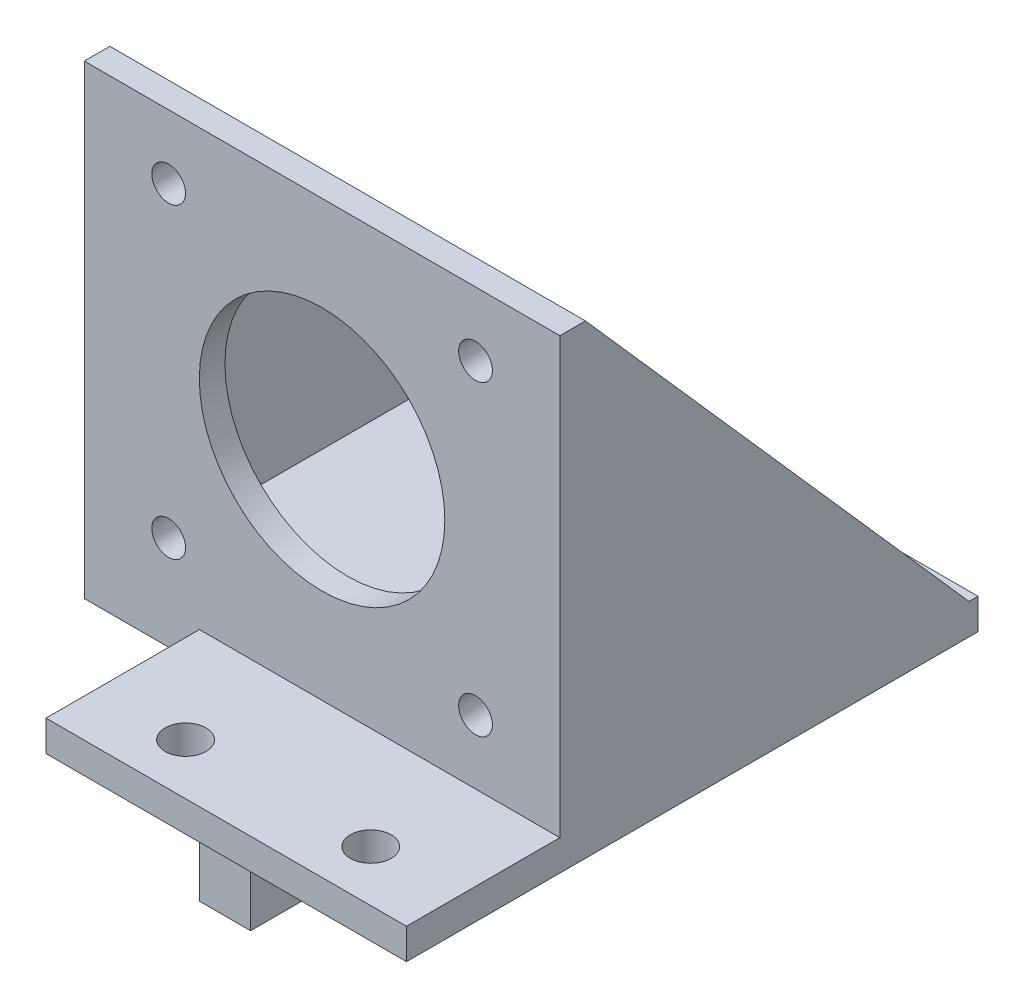
SolidWorks part; units mm, degrees
ref_plane "Front Plane" through (0, 0, 0) normal (0, 0, 1) x (1, 0, 0)
ref_plane "Top Plane" through (0, 0, 0) normal (0, 1, 0) x (1, 0, 0)
ref_plane "Right Plane" through (0, 0, 0) normal (1, 0, 0) x (0, 0, -1)
sketch "Sketch1" plane through (0, 0, 0) normal (0, 1, 0) x (1, 0, 0)
  line L0 (54.5, 40.8749) -> (54.5, 0.8749)
  line L1 (54.5, 0.8749) -> (54.5, -15)
  line L2 (0, 0) -> (0, 40.8749)
  line L3 (54.5, 40.8749) -> (0, 40.8749)
  line L4 (54.5, -15) -> (19.2596, -15)
  line L5 (0, 0) -> (19.2596, 0)
  line L10 (8, 0) -> (8, 40.8749)
  line L13 (19.2596, 0) -> (19.2596, -15)
  circle A0 centre (157.5872, -172.3849) radius 2
  circle A3 centre (151.85, -194.4993) radius 2
  circle A4 centre (46.0094, -10) radius 2
  circle A5 centre (27.9042, -10) radius 2
  point P7 (0, 0)
  point P8 (46.0094, -10)
  point P9 (27.9042, -10)
  dimension "D3" = 54.5
  dimension "D2" = 8
  dimension "D8" = 15
  dimension "D9" = 40
  dimension "D10" = 5
  dimension "D11" = 5
extrude "Boss-Extrude1" add sketch "Sketch1" along normal blind 3
sketch "Sketch2" plane through (0, 3, 0) normal (0, 1, 0) x (1, 0, 0)
  line L0 (41, 40) -> (41, 0) construction
  line L4 (10, 40) -> (10, 0)
  line L5 (41, 20) -> (8, 20) construction
  line L6 (82, 14.7564) -> (54.5, 14.7564) construction
  line L7 (8, 40) -> (8, 0)
  line L8 (54.5, 40) -> (54.5, 0)
  line L9 (14, 0) -> (82, 0)
  line L10 (52.5, 40) -> (52.5, 0)
  line L11 (10, 2.5) -> (52.5, 2.5)
  line L12 (0, 0) -> (14, 0)
  line L13 (14, 0) -> (14, -10)
  line L14 (14, -10) -> (82, -10)
  line L15 (82, -10) -> (82, 40)
  line L16 (82, 40) -> (0, 40)
  line L17 (0, 40) -> (0, 0)
  dimension "D2" = 2
  dimension "D3" = 42.5
  dimension "D1" = 2
extrude "Boss-Extrude2" add sketch "Sketch2" along normal blind 42.5
sketch "Sketch3" plane through (54.5, 0, 0) normal (1, 0, 0) x (0, 0, -1)
  line L0 (2.5, 45.5) -> (40, 3)
  line L5 (0, 3) -> (40, 3)
  line L8 (40, 3) -> (40, 45.5)
  line L10 (40, 45.5) -> (0, 45.5)
  line L11 (0, 45.5) -> (0, 3)
  dimension "D2" = 2.5
extrude "Cut-Extrude1" cut sketch "Sketch3" against normal through all
sketch "Sketch4" plane through (0, 0, 0) normal (0, 0, 1) x (1, 0, 0)
  line L0 (10, 45.5) -> (52.5, 3) construction
  line L1 (52.5, 45.5) -> (10, 3) construction
  line L8 (10, 3) -> (52.5, 3)
  line L9 (10, 45.5) -> (10, 3)
  line L10 (52.5, 45.5) -> (10, 45.5)
  line L11 (52.5, 3) -> (52.5, 45.5)
  circle A0 centre (31.25, 24.25) radius 12
  circle A1 centre (16.25, 39.25) radius 1.65
  circle A2 centre (16.25, 9.25) radius 1.65
  circle A3 centre (46.25, 9.25) radius 1.65
  circle A4 centre (46.25, 39.25) radius 1.65
  dimension "D2" = 24
  dimension "D3" = 3.3
  dimension "D4" = 30
extrude "Cut-Extrude2" cut sketch "Sketch4" against normal through all contours A0 | A2 | A1 | A4 | A3
sketch "Sketch5" plane through (0, 3, 0) normal (0, 1, 0) x (1, 0, 0)
  line L0 (0, 5) -> (8, 5)
  line L7 (55, 40.8749) -> (0, 40.8749)
  line L8 (8, 0) -> (8, 40)
  line L10 (0, 40.8749) -> (0, 0)
  line L18 (0, 0) -> (8, 0)
  line L24 (29, 0) -> (29, -15)
  line L26 (10, 2.5) -> (52.5, 2.5)
  line L28 (52.5, 2.5) -> (52.5, 40)
  line L30 (52.5, 40) -> (54.5, 40)
  line L32 (54.5, 40) -> (54.5, 0)
  line L34 (54.5, 0) -> (29, 0)
  line L36 (29, -15) -> (55, -15)
  line L38 (55, -8.3942) -> (55, 40.8749)
  line L42 (10, 40) -> (10, 2.5)
  line L43 (8, 40) -> (10, 40)
  line L45 (55, -15) -> (55, -11.6058)
  arc A2 (55, -8.3942) -> (55, -11.6058) centre (53.8077, -10) ccw
sketch "Sketch6" plane through (0, 0, 0) normal (0, -1, 0) x (1, 0, 0)
  line L0 (55, -40.8749) -> (0, -40.8749) construction
  line L1 (24.2596, -40.8749) -> (19.2596, -40.8749)
  line L2 (24.2596, -40.8749) -> (24.2596, 0)
  line L3 (24.2596, 0) -> (19.2596, 0)
  line L4 (19.2596, -40.8749) -> (19.2596, 0)
  dimension "D1" = 5
extrude "Boss-Extrude3" add sketch "Sketch6" along normal blind 20
sketch "Sketch7" plane through (24.2596, 0, 0) normal (1, 0, 0) x (0, 0, -1)
  line L0 (40.8749, -10) -> (0, -10) construction
  line L1 (40.8749, -20) -> (40.8749, 0) construction
  line L2 (0, -20) -> (0, 0) construction
  circle A0 centre (35, -10) radius 2.025
  circle A1 centre (20, -10) radius 2.025
  circle A2 centre (5, -10) radius 2.025
  dimension "D1" = 4.05
  dimension "D2" = 4.05
  dimension "D3" = 4.05
  dimension "D4" = 15
  dimension "D5" = 15
  dimension "D6" = 5
extrude "Cut-Extrude4" cut sketch "Sketch7" against normal through all
